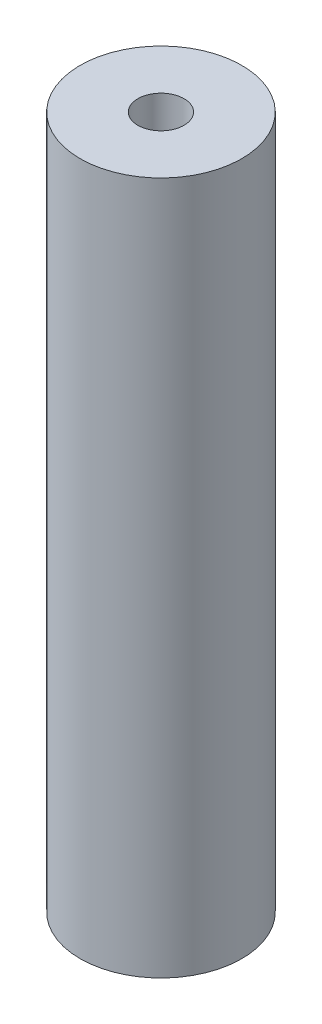
SolidWorks part; units mm, degrees
ref_plane "Front Plane" through (0, 0, 0) normal (0, 0, 1) x (1, 0, 0)
ref_plane "Top Plane" through (0, 0, 0) normal (0, 1, 0) x (1, 0, 0)
ref_plane "Right Plane" through (0, 0, 0) normal (1, 0, 0) x (0, 0, -1)
sketch "Sketch1" plane through (0, 0, 0) normal (0, 1, 0) x (1, 0, 0)
  circle A0 centre (0, 0) radius 8.75
extrude "Boss-Extrude1" add sketch "Sketch1" along normal blind 75
sketch "Sketch2" plane through (0, 0, 0) normal (0, 1, 0) x (1, 0, 0)
  circle A0 centre (0, 0) radius 2.5
extrude "Cut-Extrude1" cut sketch "Sketch2" along normal blind 131
